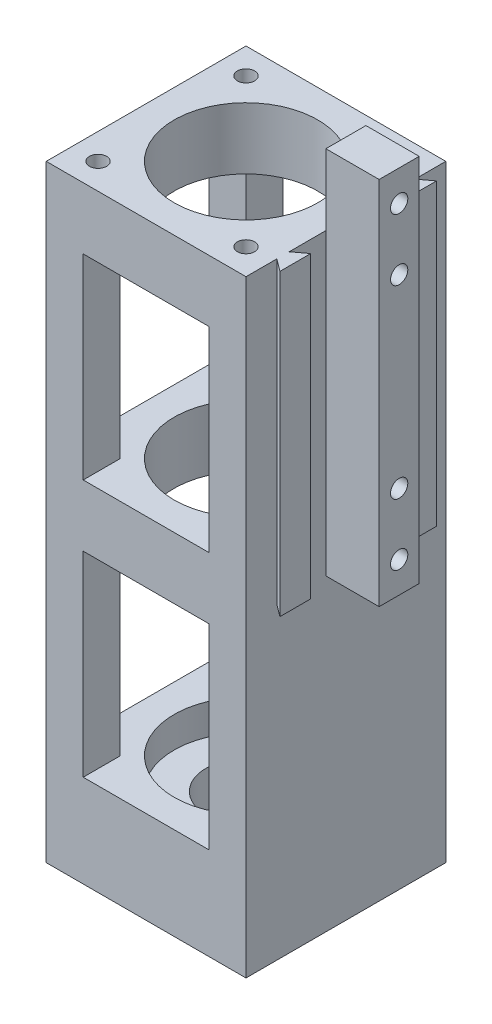
SolidWorks part; units mm, degrees
ref_plane "Front Plane" through (0, 0, 0) normal (0, 0, 1) x (1, 0, 0)
ref_plane "Top Plane" through (0, 0, 0) normal (0, 1, 0) x (1, 0, 0)
ref_plane "Right Plane" through (0, 0, 0) normal (1, 0, 0) x (0, 0, -1)
sketch "Sketch1" plane through (0, 0, 0) normal (0, 1, 0) x (1, 0, 0)
  line L0 (9.4697, -8.9895) -> (11.4697, -7.4895)
  line L1 (-22.9303, -3.9895) -> (9.4697, -3.9895)
  line L2 (-22.9303, -3.9895) -> (-22.9303, -36.3895)
  line L3 (-22.9303, -36.3895) -> (9.4697, -36.3895)
  line L4 (9.4697, -3.9895) -> (9.4697, -36.3895)
  line L5 (11.4697, -7.4895) -> (11.4697, -12.4895)
  line L6 (11.4697, -12.4895) -> (9.4697, -10.9895)
  line L7 (9.4697, -10.9895) -> (9.4697, -8.9895)
  line L8 (9.4697, -29.3895) -> (11.4697, -27.8895)
  line L9 (11.4697, -27.8895) -> (11.4697, -32.8895)
  line L10 (11.4697, -32.8895) -> (9.4697, -31.3895)
  line L11 (9.4697, -31.3895) -> (9.4697, -29.3895)
  line L12 (11.4697, -9.9895) -> (9.4697, -9.9895) construction
  line L13 (11.4697, -30.3895) -> (9.4697, -30.3895) construction
  dimension "D1" = 32.4
  dimension "D2" = 32.4
  dimension "D3" = 5
  dimension "D4" = 2
  dimension "D5" = 5
  dimension "D6" = 2
  dimension "D7" = 2
  dimension "D8" = 5
  dimension "D9" = 5
extrude "Boss-Extrude1" add sketch "Sketch1" along normal blind 98.5 contours L4 L1 L2 L3 | L10 L9 L8 L4 | L6 L5 L0 L4
sketch "Sketch2" plane through (0, 98.5, 0) normal (0, 1, 0) x (1, 0, 0)
  line L0 (-22.9303, -3.9895) -> (9.4697, -3.9895) construction
  line L1 (-6.7303, -3.9895) -> (-6.7303, -20.1895) construction
  line L2 (-6.7303, -20.1895) -> (9.4697, -20.1895) construction
  line L3 (9.4697, -10.9895) -> (9.4697, -29.3895) construction
  circle A0 centre (-6.7303, -20.1895) radius 11.65
  dimension "D1" = 23.3
extrude "Cut-Extrude1" cut sketch "Sketch2" against normal blind 88.5
sketch "Sketch3" plane through (0, 10, 0) normal (0, 1, 0) x (1, 0, 0)
  circle A0 centre (-6.7303, -20.1895) radius 6.5
  circle A1 centre (-6.7303, -20.1895) radius 11.65 construction
  dimension "D1" = 13
extrude "Cut-Extrude2" cut sketch "Sketch3" against normal through all
hole_wizard "Ø1.0mm Dowel Hole1" positions "Sketch6" profile "Sketch5" hole size "Ø1.0" standard "ANSI Metric"
sketch "Sketch6" plane through (0, 98.5, 0) normal (0, 1, 0) x (1, 0, 0)
  line L0 (-18.7303, -32.1895) -> (5.2697, -32.1895) construction
  line L1 (5.2697, -32.1895) -> (5.2697, -8.1895) construction
  line L2 (5.2697, -8.1895) -> (-18.7303, -8.1895) construction
  line L3 (-18.7303, -8.1895) -> (-18.7303, -32.1895) construction
  line L16 (5.2697, -8.1895) -> (5.2697, -3.9895) construction
  line L17 (-22.9303, -3.9895) -> (9.4697, -3.9895) construction
  line L20 (-18.7303, -32.1895) -> (-18.7303, -36.3895) construction
  line L21 (-22.9303, -36.3895) -> (9.4697, -36.3895) construction
  line L24 (-18.7303, -36.3895) -> (-22.9303, -36.3895)
  line L26 (5.2697, -3.9895) -> (9.4697, -3.9895) construction
  point P0 (-18.7303, -8.1895)
  point P2 (5.2697, -8.1895)
  point P4 (5.2697, -32.1895)
  point P6 (-18.7303, -32.1895)
  dimension "D1" = 24
  dimension "D2" = 24
sketch "Sketch5" plane through (-18.7303, 98.5, 8.1895) normal (1, 0, 0) x (0, 0, 1)
  line L0 (0, 0) -> (0, 7.8412)
  line L1 (0, 7.8412) -> (1.4, 7)
  line L2 (1.4, 7) -> (1.4, 0)
  line L5 (1.4, 0) -> (0, 0)
  line L10 (0, 7.8412) -> (-1.4, 7) construction
  line L11 (0, -6.35) -> (0, 107.95) construction
  dimension "Hole Dia." = 2.8
  dimension "Hole Depth" = 7
  dimension "Drill Angle" = 118
sketch "Sketch7" plane through (0, 0, 3.9895) normal (0, 0, -1) x (-1, 0, 0)
  line L1 (13.2303, 10) -> (0.2303, 10) construction
  line L2 (-9.4697, 0) -> (22.9303, 0) construction
  line L3 (6.7303, 0) -> (6.7303, 4.5) construction
  circle A0 centre (6.7303, 4.5) radius 2.5
  dimension "D1" = 5
  dimension "D2" = 5.5
extrude "Cut-Extrude3" cut sketch "Sketch7" against normal blind 14
sketch "Sketch8" plane through (9.4697, 0, 0) normal (1, 0, 0) x (0, 0, -1)
  line L0 (-10.9895, 0) -> (-29.3895, 0) construction
  line L1 (-16.9395, 0) -> (-23.4395, 0)
  line L2 (-16.9395, 0) -> (-16.9395, 98.5)
  line L3 (-16.9395, 98.5) -> (-23.4395, 98.5)
  line L4 (-23.4395, 0) -> (-23.4395, 98.5)
  line L5 (-10.9895, 98.5) -> (-29.3895, 98.5) construction
  line L6 (-16.9395, 0) -> (-3.9895, 0) construction
  line L7 (-23.4395, 0) -> (-36.3895, 0) construction
  dimension "D1" = 6.5
extrude "Boss-Extrude2" add sketch "Sketch8" along normal blind 8.64
sketch "Sketch14" plane through (0, 0, 0) normal (0, -1, 0) x (1, 0, 0)
  line L0 (-22.9303, 3.9895) -> (9.4697, 3.9895) construction
  line L1 (9.4697, 36.3895) -> (40.4258, 36.3895)
  line L2 (9.4697, 36.3895) -> (9.4697, 3.9895)
  line L3 (9.4697, 3.9895) -> (40.4258, 3.9895)
  line L4 (40.4258, 36.3895) -> (40.4258, 3.9895)
  dimension "D1" = 30.9561
extrude "Cut-Extrude6" cut sketch "Sketch14" against normal blind 50
sketch "Sketch11" plane through (0, 0, 36.3895) normal (0, 0, 1) x (1, 0, 0)
  line L0 (9.4697, 98.5) -> (9.4697, 0) construction
  line L1 (3.4697, 88.5) -> (-16.9303, 88.5)
  line L2 (3.4697, 88.5) -> (3.4697, 15)
  line L3 (3.4697, 15) -> (-16.9303, 15)
  line L4 (-16.9303, 88.5) -> (-16.9303, 15)
  line L5 (-22.9303, 98.5) -> (9.4697, 98.5) construction
  line L6 (-22.9303, 98.5) -> (-22.9303, 0) construction
  line L7 (-22.9303, 0) -> (9.4697, 0) construction
  line L13 (3.4697, 46.75) -> (-16.9303, 46.75)
  line L14 (3.4697, 46.75) -> (3.4697, 56.75)
  line L15 (3.4697, 56.75) -> (-16.9303, 56.75)
  line L16 (-16.9303, 46.75) -> (-16.9303, 56.75)
  point P16 (3.4697, 51.75)
  point P17 (3.4697, 51.75)
  point P18 (-16.9303, 51.75)
  point P19 (-16.9303, 51.75)
  dimension "D1" = 6
  dimension "D2" = 10
  dimension "D3" = 6
  dimension "D4" = 15
  dimension "D5" = 10
extrude "Cut-Extrude4" cut sketch "Sketch11" against normal through all contours L15 L2 L1 L4 | L2 L13 L4 L3
sketch "Sketch12" plane through (-22.9303, 0, 0) normal (-1, 0, 0) x (0, 0, 1)
  line L0 (3.9895, 98.5) -> (3.9895, 0) construction
  line L1 (9.9895, 88.5) -> (30.3895, 88.5)
  line L2 (9.9895, 88.5) -> (9.9895, 15)
  line L3 (9.9895, 15) -> (30.3895, 15)
  line L4 (30.3895, 88.5) -> (30.3895, 15)
  line L5 (36.3895, 98.5) -> (36.3895, 0) construction
  line L6 (3.9895, 0) -> (36.3895, 0) construction
  line L7 (3.9895, 98.5) -> (36.3895, 98.5) construction
  line L9 (30.3895, 46.75) -> (9.9895, 46.75)
  line L10 (30.3895, 46.75) -> (30.3895, 56.75)
  line L11 (30.3895, 56.75) -> (9.9895, 56.75)
  line L12 (9.9895, 46.75) -> (9.9895, 56.75)
  point P16 (30.3895, 51.75)
  point P17 (30.3895, 51.75)
  point P18 (9.9895, 51.75)
  point P19 (9.9895, 51.75)
  dimension "D1" = 6
  dimension "D2" = 6
  dimension "D3" = 15
  dimension "D4" = 10
  dimension "D5" = 10
extrude "Cut-Extrude5" cut sketch "Sketch12" against normal blind 15 contours L11 L4 L1 L2 | L4 L9 L2 L3
sketch "Sketch23" plane through (0, 98.5, 0) normal (0, 1, 0) x (1, 0, 0)
  line L1 (9.4697, -23.4395) -> (18.1097, -23.4395)
  line L2 (9.4697, -23.4395) -> (9.4697, -16.9395)
  line L3 (9.4697, -16.9395) -> (18.1097, -16.9395)
  line L4 (18.1097, -23.4395) -> (18.1097, -16.9395)
extrude "Boss-Extrude3" add sketch "Sketch23" along normal blind 11.5
hole_wizard "Ø1.0mm Dowel Hole3" positions "Sketch21" profile "Sketch22" hole size "Ø1.0" standard "ANSI Metric"
sketch "Sketch21" plane through (18.1097, 0, 0) normal (1, 0, 0) x (0, 0, -1)
  line L0 (-23.4395, 105) -> (-20.1895, 105) construction
  line L1 (-23.4395, 110) -> (-23.4395, 50) construction
  line L2 (-20.1895, 105) -> (-16.9395, 105) construction
  line L3 (-16.9395, 50) -> (-16.9395, 110) construction
  line L5 (-20.1895, 105) -> (-20.1895, 55) construction
  line L8 (-23.4395, 50) -> (-16.9395, 50) construction
  line L9 (-23.4395, 110) -> (-16.9395, 110) construction
  point P0 (-20.1895, 105)
  point P2 (-20.1895, 55)
  point P27 (-20.1895, 65)
  point P29 (-20.1895, 95)
  dimension "D1" = 5
  dimension "D2" = 5
  dimension "D3" = 10
  dimension "D4" = 10
sketch "Sketch22" plane through (18.1097, 105, 20.1895) normal (0, 1, 0) x (0, 0, -1)
  line L0 (0, 0) -> (0, 5.8412)
  line L1 (0, 5.8412) -> (1.4, 5)
  line L2 (1.4, 5) -> (1.4, 0)
  line L5 (1.4, 0) -> (0, 0)
  line L10 (0, 5.8412) -> (-1.4, 5) construction
  line L11 (0, -6.35) -> (0, 107.95) construction
  dimension "Hole Dia." = 2.8
  dimension "Hole Depth" = 5
  dimension "Drill Angle" = 118
